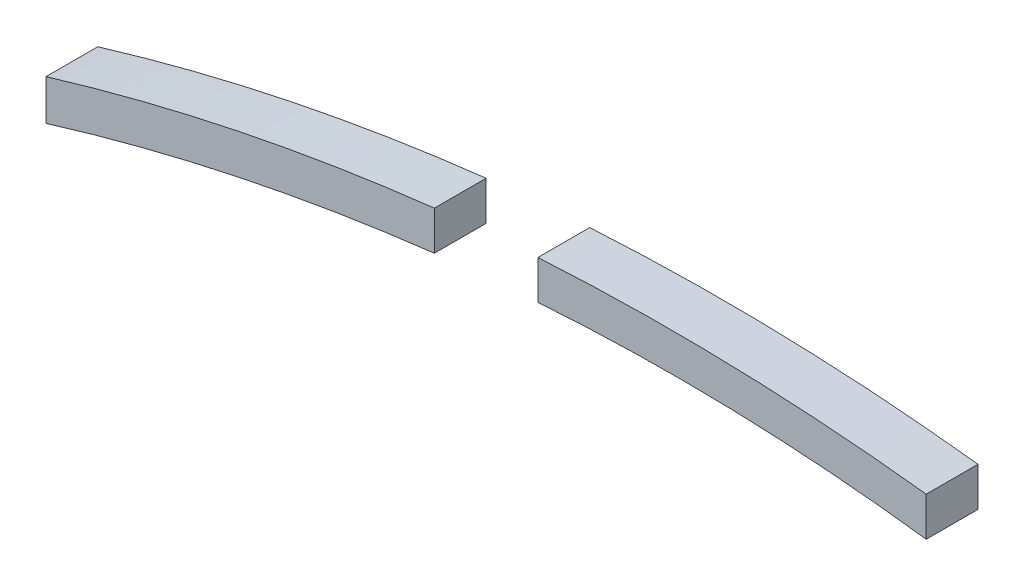
SolidWorks part; units mm, degrees
material "Silicon Rubber"
ref_plane "Front Plane" through (0, 0, 0) normal (0, 0, 1) x (1, 0, 0)
ref_plane "Top Plane" through (0, 0, 0) normal (0, 1, 0) x (1, 0, 0)
ref_plane "Right Plane" through (0, 0, 0) normal (1, 0, 0) x (0, 0, -1)
sketch "Sketch1" plane through (0, 0, 0) normal (0, 0, 1) x (1, 0, 0)
  line L0 (-55, 0) -> (60, 0) construction
  line L1 (-55, 0) -> (-55, 9) construction
  line L2 (0, 0) -> (0, 20) construction
  line L3 (60, 0) -> (60, 20) construction
  line L4 (44.96, -17.7842) -> (-154.96, 35.7842) construction
  line L5 (146.7072, 32.8352) -> (-142.1892, 7.5601) construction
  line L6 (109.9058, 61.8759) -> (-38.31, -62.4919) construction
  line L7 (-17, 16.7009) -> (-17, 15.136)
  line L8 (-2, 19.8009) -> (-2, 18.2914)
  line L9 (2, 20.1509) -> (2, 18.6479)
  line L10 (17, 19.7331) -> (17, 18.2239)
  spline S0 degree 3 poles (-55, 9) (-40.5111, 5.1177) (-23.7422, 18.0543) (25.683, 22.3227) (48.5093, 10.3582) (60, 20) knots 0 0 0 0 0.434841 0.534841 1 1 1 1
  spline S1 degree 1 poles (-55.3882, 7.5511) (60.9642, 18.8509) knots 0 0 1 1 construction
  spline S2 degree 3 poles (-55.3882, 7.5511) (-54.3038, 7.2605) (-52.0727, 6.8182) (-47.7116, 6.5188) (-42.282, 7.0636) (-35.7513, 8.7524) (-29.0388, 11.0554) (-23.3805, 13.089) (-18.6833, 14.6352) (-15.7367, 15.5221) (-11.5854, 16.6403) (-7.5895, 17.5191) (-3.4353, 18.1301) (-1.3388, 18.3687) (-0.0065, 18.4956) (1.3298, 18.6066) (3.659, 18.7571) (7.1333, 18.8536) (11.4571, 18.732) (15.1363, 18.4344) (17.9393, 18.1203) (21.9889, 17.6023) (27.9447, 16.62) (35.5921, 15.2572) (42.7636, 14.2907) (48.3291, 14.1852) (52.5241, 14.7703) (55.5283, 15.6121) (57.8957, 16.7067) (59.6833, 17.839) (60.5498, 18.5032) (60.9642, 18.8509) knots 0 0 0 0 0.03125 0.0625 0.125 0.1875 0.25 0.3125 0.33818 0.36943 0.385055 0.4375 0.461022 0.475135 0.482192 0.489249 0.503362 0.53125 0.5625 0.596265 0.61189 0.625 0.6875 0.75 0.8125 0.875 0.90625 0.9375 0.96875 0.984375 1 1 1 1
  dimension "D6" = 50
  dimension "D7" = 75
  dimension "D8" = 85
  dimension "D9" = 50
  dimension "D10" = 145
  dimension "D11" = 50
  dimension "D1" = 115
  dimension "D2" = 55
  dimension "D3" = 9
  dimension "D4" = 20
  dimension "D5" = 20
  dimension "D13" = 15
  dimension "D14" = 2
  dimension "D15" = 15
  dimension "D12" = 1.5
sketch "Sketch2" plane through (0, 0, 0) normal (0, 0, 1) x (1, 0, 0)
  line L0 (-17, 16.7009) -> (-17, 15.136)
  line L1 (-2, 19.8009) -> (-2, 18.2914)
  line L2 (17, 19.7331) -> (17, 18.2239)
  line L4 (2, 20.1509) -> (2, 18.6479)
  arc A0 (-17, 15.136) -> (-2, 18.2914) centre (7.8661, -65.842) cw
  arc A1 (-17, 16.7009) -> (-2, 19.8009) centre (7.7011, -64.9808) cw
  arc A2 (2, 18.6479) -> (17, 18.2239) centre (7.3769, -56.6827) cw
  arc A3 (2, 20.1509) -> (17, 19.7331) centre (7.1284, -65.2005) cw
extrude "Boss-Extrude1" add sketch "Sketch2" along normal blind 2
